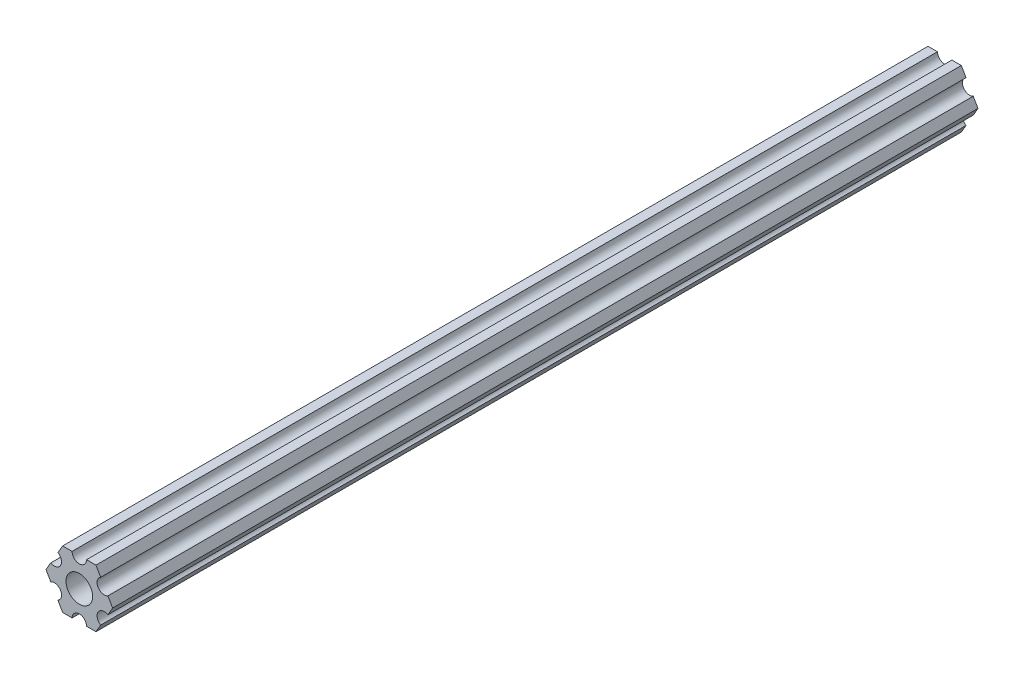
SolidWorks part; units mm, degrees
material "6061 Alloy"
ref_plane "Front Plane" through (0, 0, 0) normal (0, 0, 1) x (1, 0, 0)
ref_plane "Top Plane" through (0, 0, 0) normal (0, 1, 0) x (1, 0, 0)
ref_plane "Right Plane" through (0, 0, 0) normal (1, 0, 0) x (0, 0, -1)
ref_plane "Plane1" through (0, 0, 304.8) normal (0, 0, 1) x (1, 0, 0)
sketch "Sketch1" plane through (0, 0, 304.8) normal (0, 0, 1) x (1, 0, 0)
  line L0 (6.293, -1.8002) -> (7.3323, 0)
  line L1 (7.3323, 0) -> (6.293, 1.8002)
  line L2 (4.7055, 4.5498) -> (3.6662, 6.35)
  line L3 (3.6662, 6.35) -> (1.5875, 6.35)
  line L4 (-1.5875, 6.35) -> (-3.6662, 6.35)
  line L5 (-3.6662, 6.35) -> (-4.7055, 4.5498)
  line L6 (-6.293, 1.8002) -> (-7.3323, 0)
  line L7 (-7.3323, 0) -> (-6.293, -1.8002)
  line L8 (-4.7055, -4.5498) -> (-3.6662, -6.35)
  line L9 (-3.6662, -6.35) -> (-1.5875, -6.35)
  line L10 (1.5875, -6.35) -> (3.6662, -6.35)
  line L11 (3.6662, -6.35) -> (4.7055, -4.5498)
  arc A0 (6.293, 1.8002) -> (4.7055, 4.5498) centre (5.4993, 3.175) cw
  arc A1 (1.5875, 6.35) -> (-1.5875, 6.35) centre (0, 6.35) cw
  arc A2 (-4.7055, 4.5498) -> (-6.293, 1.8002) centre (-5.4993, 3.175) cw
  arc A3 (-6.293, -1.8002) -> (-4.7055, -4.5498) centre (-5.4993, -3.175) cw
  arc A4 (-1.5875, -6.35) -> (1.5875, -6.35) centre (0, -6.35) cw
  arc A5 (4.7055, -4.5498) -> (6.293, -1.8002) centre (5.4993, -3.175) cw
  circle A6 centre (0, 0) radius 2.9337
extrude "Boss-Extrude1" add sketch "Sketch1" against normal blind 190.5
